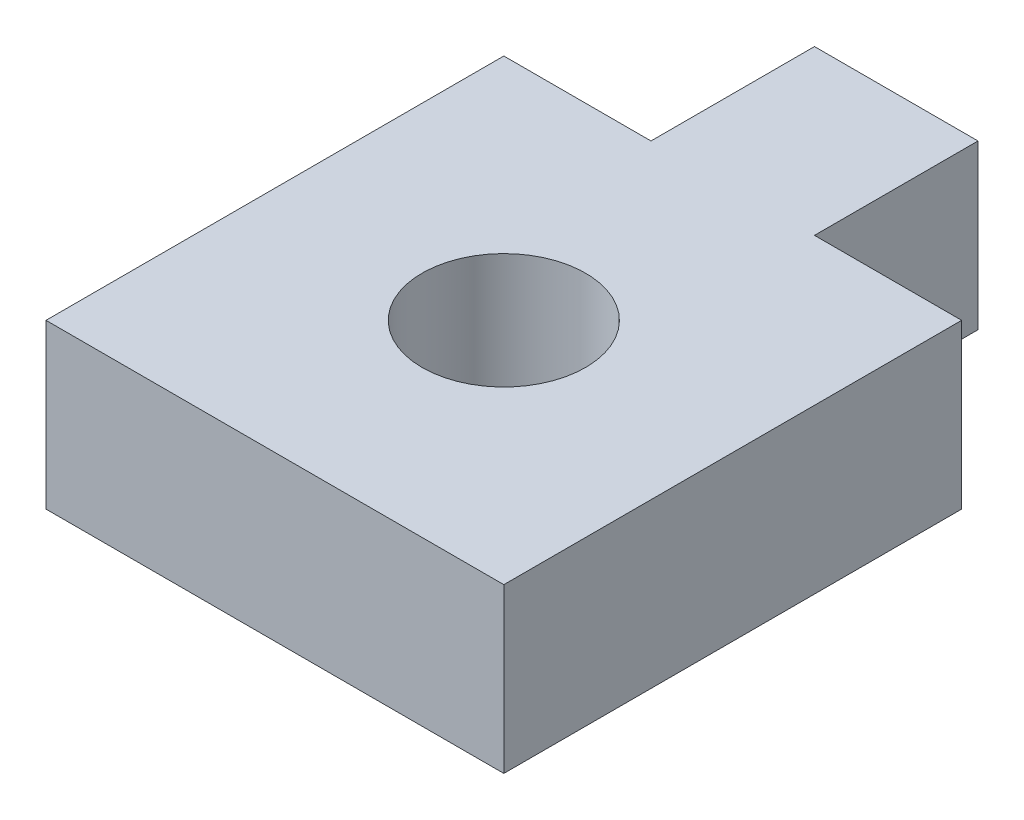
SolidWorks part; units mm, degrees
material "Pine"
ref_plane "Front Plane" through (0, 0, 0) normal (0, 0, 1) x (1, 0, 0)
ref_plane "Top Plane" through (0, 0, 0) normal (0, 1, 0) x (1, 0, 0)
ref_plane "Right Plane" through (0, 0, 0) normal (1, 0, 0) x (0, 0, -1)
sketch "Sketch1" plane through (0, 0, 0) normal (0, 1, 0) x (1, 0, 0)
  line L0 (0, 0) -> (0, 17.78)
  line L1 (0, 17.78) -> (-5.715, 17.78)
  line L2 (-5.715, 17.78) -> (-5.715, 24.13)
  line L3 (-5.715, 24.13) -> (-12.065, 24.13)
  line L4 (-12.065, 24.13) -> (-12.065, 17.78)
  line L5 (-12.065, 17.78) -> (-17.78, 17.78)
  line L6 (-17.78, 17.78) -> (-17.78, 0)
  line L7 (-17.78, 0) -> (0, 0)
  line L8 (0, 17.78) -> (-17.78, 0) construction
  circle A0 centre (-8.89, 8.89) radius 3.175
  dimension "D5" = 6.35
  dimension "D1" = 17.78
  dimension "D2" = 17.78
  dimension "D3" = 6.35
  dimension "D4" = 6.35
extrude "Boss-Extrude1" add sketch "Sketch1" along normal blind 6.35
